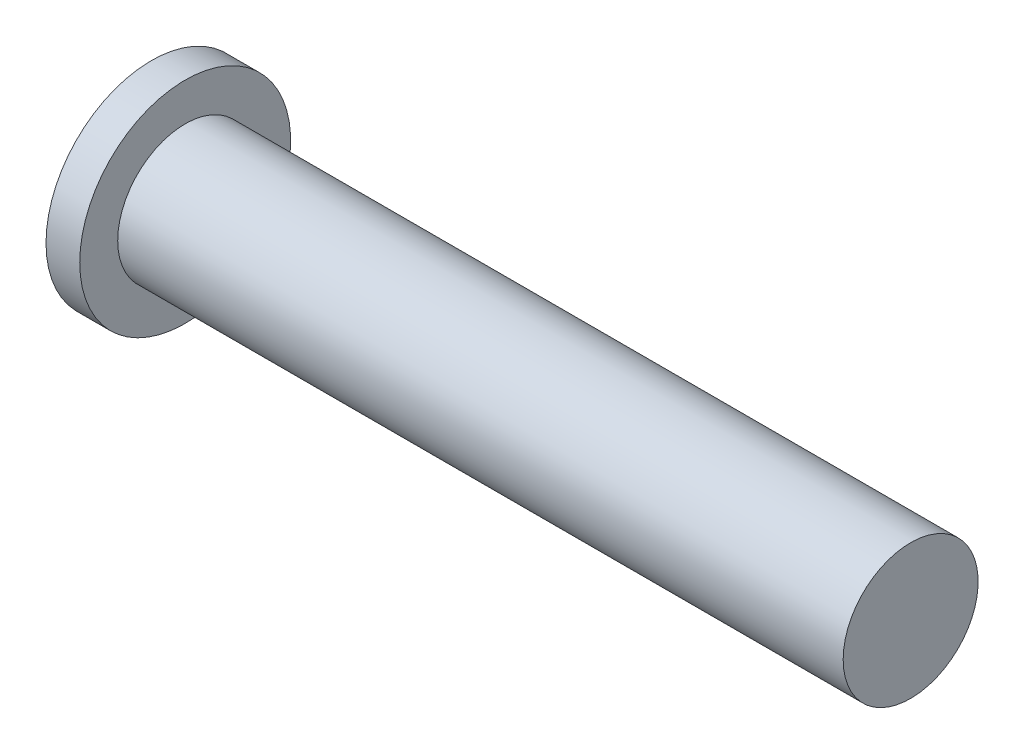
SolidWorks part; units mm, degrees
ref_plane "正面" through (0, 0, 0) normal (0, 0, 1) x (1, 0, 0)
ref_plane "平面" through (0, 0, 0) normal (0, 1, 0) x (1, 0, 0)
ref_plane "右側面" through (0, 0, 0) normal (1, 0, 0) x (0, 0, -1)
sketch "ｽｹｯﾁ1" plane through (0, 0, 0) normal (0, 1, 0) x (1, 0, 0)
  line L0 (0, 0) -> (78.1964, 0) construction
  line L1 (0, 0) -> (0, 6.25)
  line L2 (0, 6.25) -> (2, 6.25)
  line L3 (2, 6.25) -> (2, 4)
  line L4 (2, 4) -> (45, 4)
  line L5 (45, 4) -> (45, 0)
  line L6 (45, 0) -> (0, 0)
  dimension "D1" = 6.25
  dimension "D2" = 4
  dimension "D3" = 2
  dimension "D4" = 45
revolve "回転1" add sketch "ｽｹｯﾁ1" angle 360 about L0
